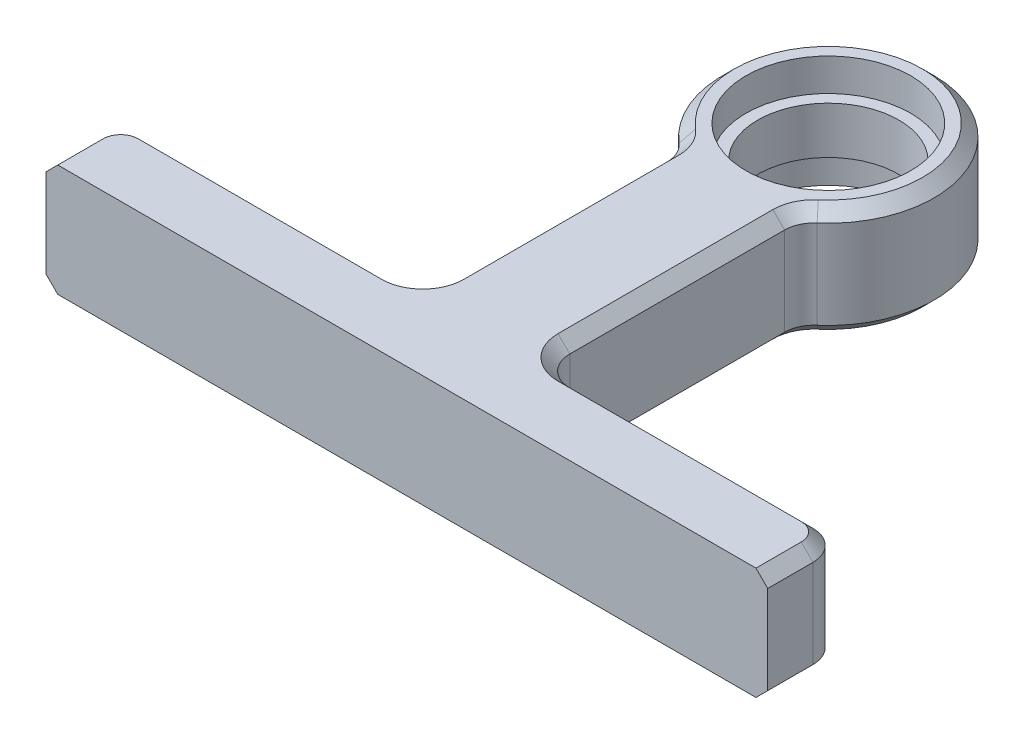
SolidWorks part; units mm, degrees
ref_plane "Front Plane" through (0, 0, 0) normal (0, 0, 1) x (1, 0, 0)
ref_plane "Top Plane" through (0, 0, 0) normal (0, 1, 0) x (1, 0, 0)
ref_plane "Right Plane" through (0, 0, 0) normal (1, 0, 0) x (0, 0, -1)
sketch "Sketch1" plane through (0, 0, 0) normal (0, 1, 0) x (1, 0, 0)
  line L0 (0, 0) -> (0, 35.825) construction
  line L13 (-30.675, 0) -> (-30.675, 6.35)
  line L20 (30.675, 0) -> (30.675, 6.35)
  line L22 (-30.675, 0) -> (30.675, 0)
  line L31 (-5, 28.3417) -> (-5, 6.35)
  line L32 (-30.675, 6.35) -> (-5, 6.35)
  line L33 (30.675, 6.35) -> (5, 6.35)
  line L34 (5, 28.3417) -> (5, 6.35)
  circle A3 centre (0, 35.825) radius 7
  arc A5 (5, 28.3417) -> (-5, 28.3417) centre (0, 35.825) ccw
  dimension "D2" = 61.35
  dimension "D3" = 6.35
  dimension "D4" = 14
  dimension "D5" = 9
  dimension "D1" = 35.825
  dimension "D6" = 10
extrude "Boss-Extrude1" add sketch "Sketch1" along normal mid plane 9.525
sketch "Sketch2" plane through (0, 4.7625, 0) normal (0, 1, 0) x (1, 0, 0)
  circle A0 centre (0, 35.825) radius 6
  circle A1 centre (0, 35.825) radius 9
  dimension "D1" = 18
  dimension "D2" = 12
fillet "Fillet1" radius 2.5 6 edges at (-5, 0, -28.3417) (5, 0, -28.3417) (30.675, 0, -6.35) (5, 0, -6.35) (-30.675, 0, -6.35) (-5, 0, -6.35)
chamfer "Chamfer1" distance 1 angle 45 26 edges at (30.675, -4.7625, -1.925) (-30.675, -4.7625, -1.925) (29.9428, -4.7625, -5.6178) (-29.9428, -4.7625, -5.6178) (17.8375, -4.7625, -6.35) (-17.8375, -4.7625, -6.35) (5.7322, -4.7625, -7.0822) (-5.7322, -4.7625, -7.0822) (5, -4.7625, -17.9786) (-5, -4.7625, -17.9786) (5.2278, -4.7625, -28.1498) (-5.2278, -4.7625, -28.1498) (0, -4.7625, -44.825) (30.675, 4.7625, -1.925) (-30.675, 4.7625, -1.925) (29.9428, 4.7625, -5.6178) (-29.9428, 4.7625, -5.6178) (17.8375, 4.7625, -6.35) (-17.8375, 4.7625, -6.35) (5.7322, 4.7625, -7.0822) (-5.7322, 4.7625, -7.0822) (5, 4.7625, -17.9786) (-5, 4.7625, -17.9786) (5.2278, 4.7625, -28.1498) (-5.2278, 4.7625, -28.1498) (0, 4.7625, -44.825)
sketch "Sketch3" plane through (0, 0, 0) normal (0, 1, 0) x (1, 0, 0)
  circle A0 centre (0, 35.825) radius 7
  circle A1 centre (0, 35.825) radius 6
  dimension "D1" = 12
extrude "Boss-Extrude2" add sketch "Sketch3" along normal mid plane 4
